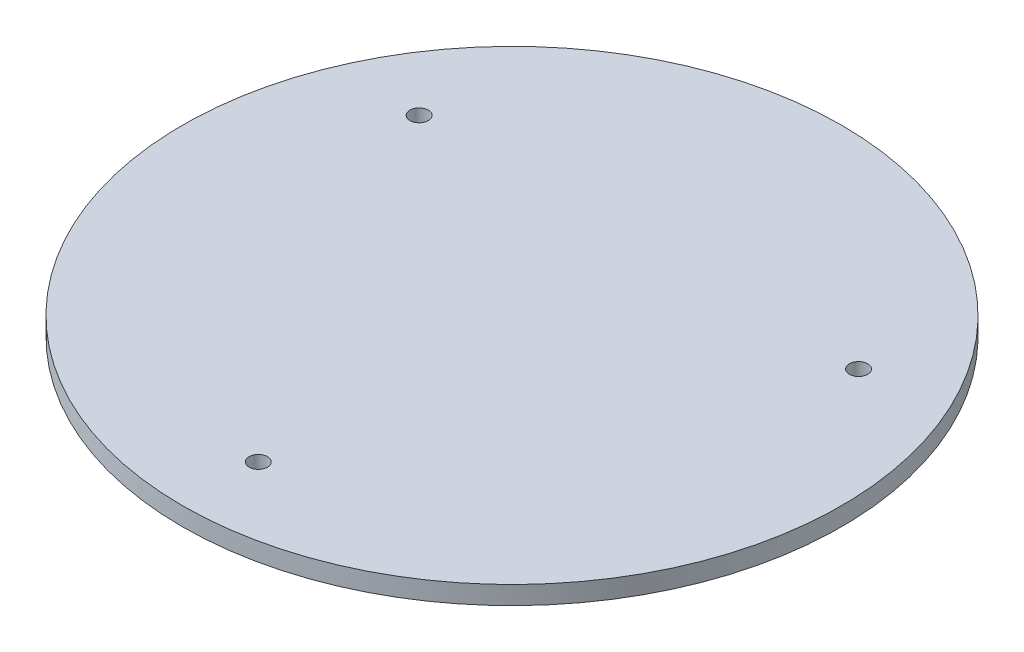
SolidWorks part; units mm, degrees
material "Acrylic (Medium-high impact)"
ref_plane "Front Plane" through (0, 0, 0) normal (0, 0, 1) x (1, 0, 0)
ref_plane "Top Plane" through (0, 0, 0) normal (0, 1, 0) x (1, 0, 0)
ref_plane "Right Plane" through (0, 0, 0) normal (1, 0, 0) x (0, 0, -1)
sketch "Sketch1" plane through (0, 0, 0) normal (0, 1, 0) x (1, 0, 0)
  circle A0 centre (0, 0) radius 57.15
  dimension "D1" = 114.3
extrude "Boss-Extrude1" add sketch "Sketch1" along normal blind 3.175
sketch "Sketch2" plane through (0, 3.175, 0) normal (0, 1, 0) x (1, 0, 0)
  line L0 (0, -43.9941) -> (38.1, 21.997) construction
  line L1 (38.1, 21.997) -> (-38.1, 21.997) construction
  line L2 (-38.1, 21.997) -> (0, -43.9941) construction
  line L3 (0, -43.9941) -> (0, 0) construction
  line L4 (0, 0) -> (38.1, 21.997) construction
  line L5 (0, 0) -> (-38.1, 21.997) construction
  circle A4 centre (0, -43.9941) radius 1.5875
  circle A6 centre (-38.1, 21.997) radius 1.5875
  circle A7 centre (38.1, 21.997) radius 1.5875
  dimension "D1" = 3.175
  dimension "D2" = 3.175
  dimension "D3" = 3.175
  dimension "D4" = 76.2
extrude "Cut-Extrude1" cut sketch "Sketch2" against normal through all
